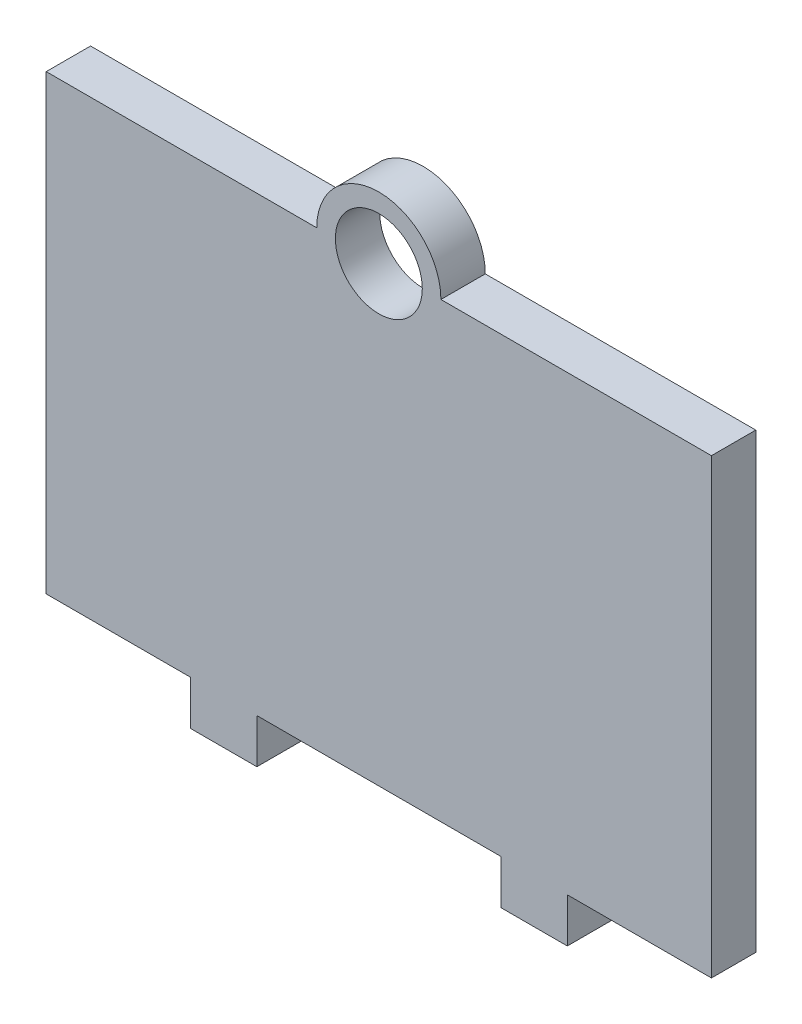
SolidWorks part; units mm, degrees
material "Acrylic (Medium-high impact)"
ref_plane "Front Plane" through (0, 0, 0) normal (0, 0, 1) x (1, 0, 0)
ref_plane "Top Plane" through (0, 0, 0) normal (0, 1, 0) x (1, 0, 0)
ref_plane "Right Plane" through (0, 0, 0) normal (1, 0, 0) x (0, 0, -1)
sketch "Sketch1" plane through (0, 0, 0) normal (0, 0, 1) x (1, 0, 0)
  line L0 (53.975, 0) -> (34.925, 0) construction
  line L1 (-95.25, 142.24) -> (-17.78, 142.24)
  line L2 (-95.25, 142.24) -> (-95.25, 12.7)
  line L3 (-95.25, 12.7) -> (-53.975, 12.7)
  line L4 (95.25, 142.24) -> (95.25, 12.7)
  line L5 (53.975, 0) -> (53.975, 12.7) construction
  line L6 (34.925, 0) -> (34.925, 12.7) construction
  line L7 (-34.925, 0) -> (-53.975, 0) construction
  line L8 (-34.925, 0) -> (-34.925, 12.7) construction
  line L9 (-53.975, 0) -> (-53.975, 12.7) construction
  line L10 (53.975, 0) -> (34.925, 0)
  line L11 (53.975, 0) -> (53.975, 12.7)
  line L12 (34.925, 0) -> (34.925, 12.7)
  line L13 (-34.925, 0) -> (-53.975, 0)
  line L14 (-34.925, 0) -> (-34.925, 12.7)
  line L15 (-53.975, 0) -> (-53.975, 12.7)
  line L16 (-34.925, 12.7) -> (34.925, 12.7)
  line L17 (53.975, 12.7) -> (95.25, 12.7)
  line L18 (17.78, 142.24) -> (95.25, 142.24)
  line L19 (95.25, 12.7) -> (95.25, 0) construction
  circle A0 centre (0, 142.24) radius 12.446
  arc A1 (17.78, 142.24) -> (-17.78, 142.24) centre (0, 142.24) ccw
  dimension "D1" = 24.892
  dimension "D2" = 35.56
extrude "Extrude1" add sketch "Sketch1" against normal blind 12.7
